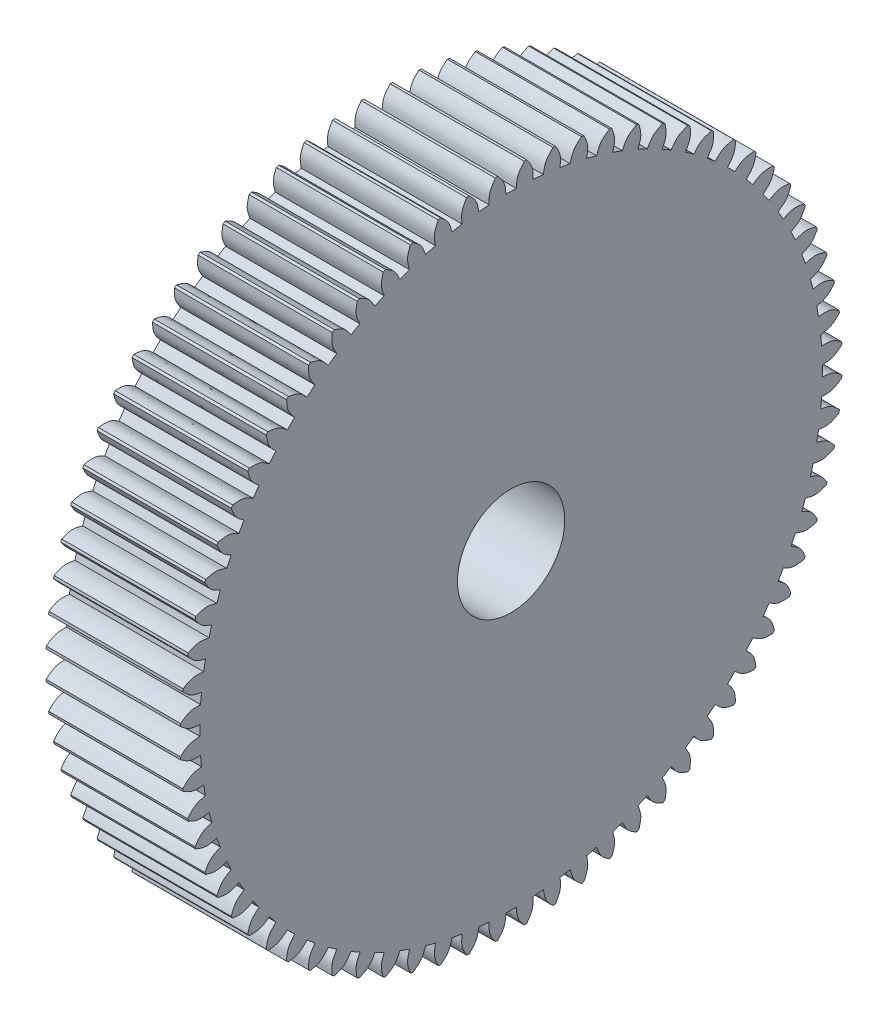
SolidWorks part; units mm, degrees
ref_plane "Front" through (0, 0, 0) normal (0, 0, 1) x (1, 0, 0)
ref_plane "Top" through (0, 0, 0) normal (0, 1, 0) x (1, 0, 0)
ref_plane "Right" through (0, 0, 0) normal (1, 0, 0) x (0, 0, -1)
sketch "Ritning 1" plane through (0, 0, 0) normal (0, 0, 1) x (1, 0, 0)
  line L0 (-7.5, -18.5) -> (7.5, -18.5) construction
  line L1 (-7.5, -12.5) -> (7.5, -12.5)
  line L2 (7.5, 18.5) -> (7.5, -12.5)
  line L3 (7.5, 18.5) -> (-7.5, 18.5)
  line L4 (-7.5, 18.5) -> (-7.5, -12.5)
  line L5 (-7.5, -12.5) -> (-7.5, -18.5) construction
  line L6 (-7.5, -18.5) -> (7.5, -18.5) construction
  dimension "D1" = 7.5
  dimension "D2" = 7.5
  dimension "D3" = 18.5
  dimension "D4" = 12.5
  dimension "D5" = 18.5
revolve "Kugghjulsämne" add sketch "Ritning 1" angle 360 about L0
sketch "Ritning 2" plane through (-7.5, 0, 0) normal (-1, 0, 0) x (0, 0, 1)
  line L0 (0, -18.5) -> (0, 18.5) construction
  line L1 (1.4711, 18.4707) -> (0, 19.9419)
  line L2 (-1.4711, 18.4707) -> (0, 19.9419)
  line L3 (0, -18.5) -> (5.8677, -18.5) construction
  arc A0 (0.5745, 16.2953) -> (-0.5745, 16.2953) centre (0, -18.5) ccw
  circle A1 centre (0, -18.5) radius 37 construction
  spline S0 degree 3 poles (1.4711, 18.4707) (1.203, 18.1607) (0.6625, 17.5356) (0.604, 16.7109) (0.5745, 16.2953) knots 0 0 0 0 0.496036 1 1 1 1
  spline S1 degree 3 poles (-1.4711, 18.4707) (-1.203, 18.1607) (-0.6625, 17.5356) (-0.604, 16.7109) (-0.5745, 16.2953) knots 0 0 0 0 0.496036 1 1 1 1
  dimension "D1" = 34.8
  dimension "D2" = 0.5745
  dimension "D3" = 0.7854
  dimension "D4" = 1.4711
  dimension "D5" = 35.9914
  dimension "D6" = 0.7854
  dimension "D7" = 36.9707
extrude "Kugglucka" cut sketch "Ritning 2" against normal up to surface (15 mm away) up to face at (7.5, -18.5, 37)
pattern_circular "CirPattern" count 72 over 360 about axis through (-7.5, -18.5, 0) along (-1, 0, 0) of "Kugglucka"
